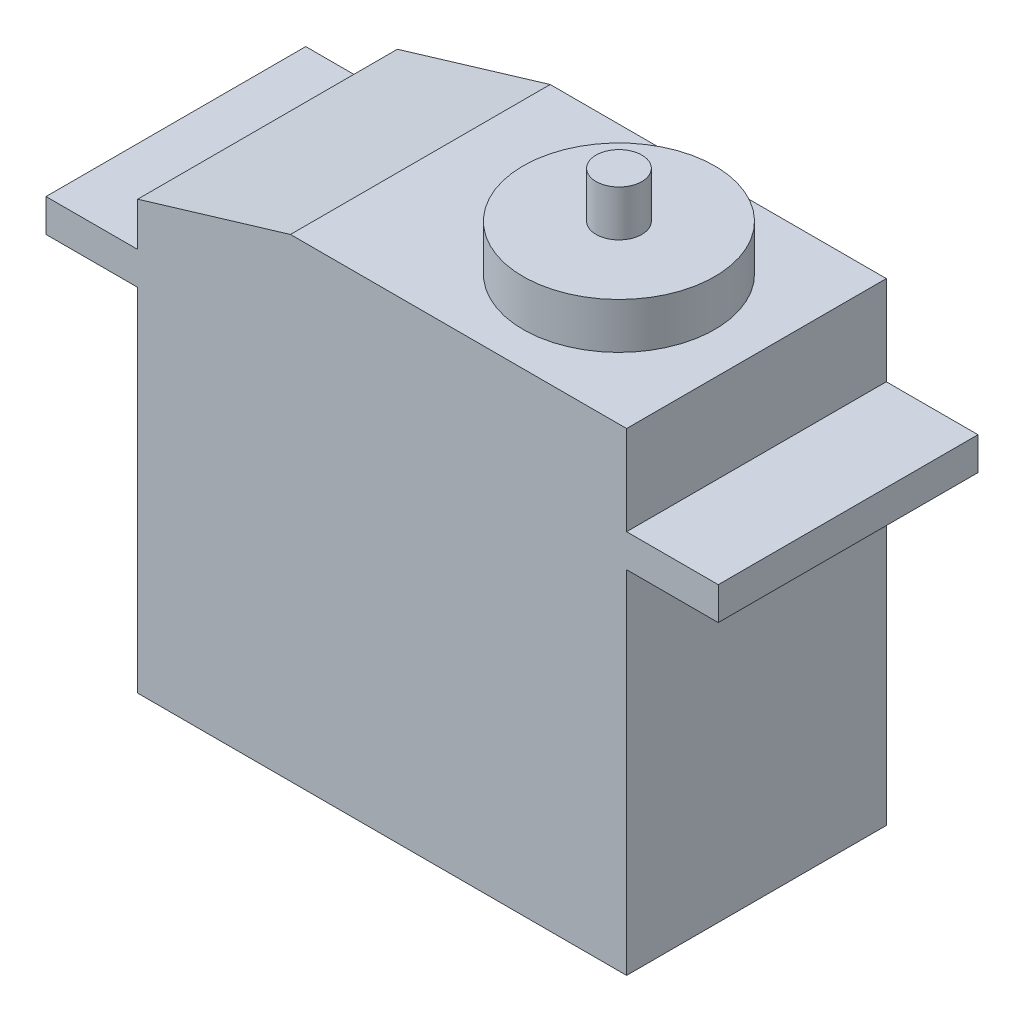
SolidWorks part; units mm, degrees
ref_plane "Спереди" through (0, 0, 0) normal (0, 0, 1) x (1, 0, 0)
ref_plane "Сверху" through (0, 0, 0) normal (0, 1, 0) x (1, 0, 0)
ref_plane "Справа" through (0, 0, 0) normal (1, 0, 0) x (0, 0, -1)
other "Configuration Table"
sketch "Sketch1" plane through (0, 0, 0) normal (0, 0, 1) x (1, 0, 0)
  line L0 (0, -16.9643) -> (0, 16.9643) construction
  line L1 (28.9758, 0) -> (-28.9758, 0) construction
  line L2 (-16, -15.5) -> (-16, 12.5)
  line L3 (-16, -15.5) -> (16, -15.5)
  line L4 (-16, -15.5) -> (-16, 12.5)
  line L5 (-6, 15.5) -> (16, 15.5)
  line L6 (16, -15.5) -> (16, 15.5)
  line L7 (-16, -15.5) -> (16, 15.5) construction
  line L8 (-13.6355, 13.2094) -> (16, -15.5) construction
  line L9 (-16, 12.5) -> (-6, 15.5)
  point P0 (0, 0)
  point P4 (0, 0)
  point P7 (0, 0)
  point P10 (0, 0)
  dimension "D1" = 31
  dimension "D2" = 32
  dimension "D3" = 28
  dimension "D4" = 10
  dimension "D5" = 15.5
extrude "Boss-Extrude1" add sketch "Sketch1" against normal blind 17 contours L9 L2 L3 L6 L5
ref_plane "Plane3" through (0, 7.5, 0) normal (0, 1, 0) x (1, 0, 0)
sketch "Sketch2" plane through (0, 7.5, 0) normal (0, 1, 0) x (1, 0, 0)
  line L0 (-16, 17) -> (-16, 0) construction
  line L1 (-22, 17) -> (22, 17)
  line L2 (-22, 17) -> (-22, 0)
  line L3 (-22, 0) -> (22, 0)
  line L4 (22, 17) -> (22, 0)
  dimension "D1" = 44
  dimension "D2" = 17
  dimension "D3" = 6
extrude "Boss-Extrude2" add sketch "Sketch2" along normal blind 2.15
sketch "Sketch3" plane through (0, 15.5, 0) normal (0, 1, 0) x (1, 0, 0)
  line L0 (16, 17) -> (16, 0) construction
  line L1 (-6, 0) -> (16, 0) construction
  circle A0 centre (7, 8.5) radius 6.275
  dimension "D1" = 12.55
  dimension "D2" = 9
  dimension "D3" = 8.5
extrude "Boss-Extrude3" add sketch "Sketch3" along normal blind 3
sketch "Sketch4" plane through (0, 18.5, 0) normal (0, 1, 0) x (1, 0, 0)
  circle A0 centre (7, 8.5) radius 1.5
  dimension "D1" = 3
extrude "Boss-Extrude4" add sketch "Sketch4" along normal blind 3
